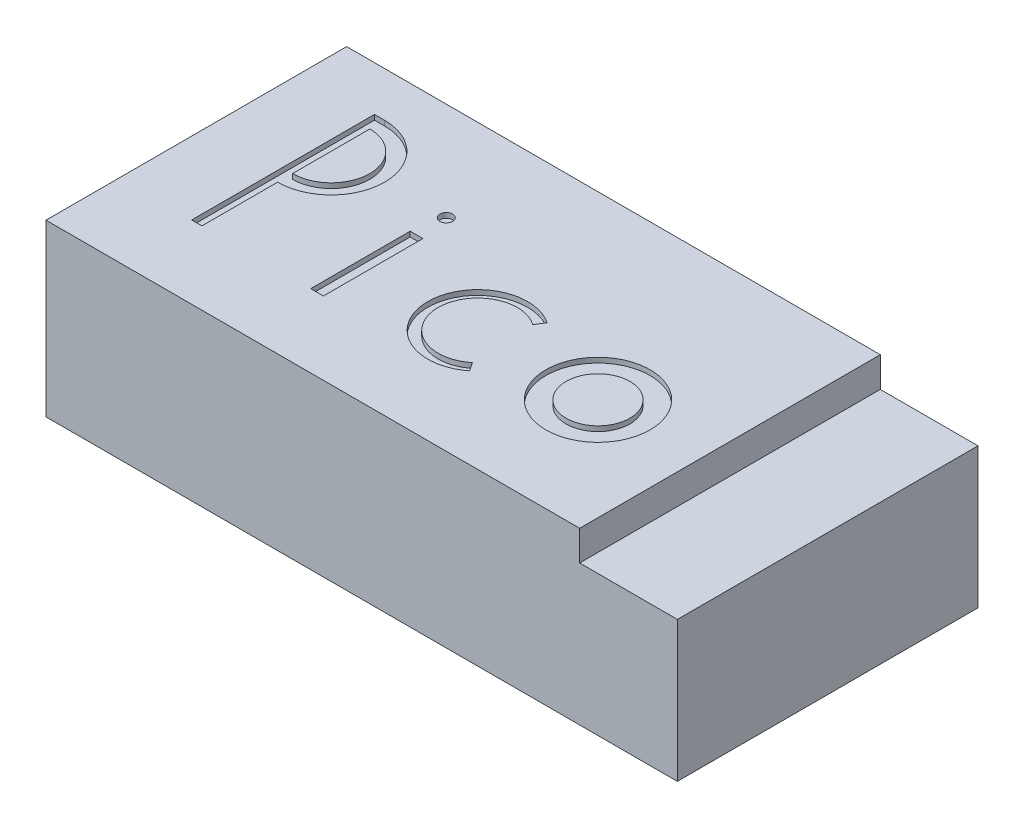
SolidWorks part; units mm, degrees
ref_plane "Front Plane" through (0, 0, 0) normal (0, 0, 1) x (1, 0, 0)
ref_plane "Top Plane" through (0, 0, 0) normal (0, 1, 0) x (1, 0, 0)
ref_plane "Right Plane" through (0, 0, 0) normal (1, 0, 0) x (0, 0, -1)
sketch "Sketch1" plane through (0, 0, 0) normal (0, 1, 0) x (1, 0, 0)
  line L0 (0, 0) -> (126, 0)
  line L1 (126, 0) -> (126, 60)
  line L2 (126, 60) -> (0, 60)
  line L3 (0, 60) -> (0, 0)
  dimension "D1" = 126
  dimension "D2" = 60
extrude "Boss-Extrude1" add sketch "Sketch1" along normal blind 28
sketch "Sketch2" plane through (0, 28, 0) normal (0, 1, 0) x (1, 0, 0)
  line L0 (0, 0) -> (106.5, 0)
  line L1 (0, 0) -> (126, 0) construction
  line L2 (106.5, 0) -> (106.5, 60)
  line L3 (126, 60) -> (0, 60) construction
  line L4 (106.5, 60) -> (0, 60)
  line L5 (0, 60) -> (0, 0)
  dimension "D1" = 106.5
extrude "Boss-Extrude2" add sketch "Sketch2" along normal blind 6
sketch "Sketch3" plane through (0, 34, 0) normal (0, 1, 0) x (1, 0, 0)
  line L0 (14.4991, 40.4296) -> (14.4991, 14.5795)
  line L1 (14.4991, 14.5795) -> (16.5467, 14.5795)
  line L2 (16.5467, 14.5795) -> (16.5467, 29.6801)
  line L3 (14.4991, 40.4296) -> (14.4991, 51.0512)
  line L4 (14.4991, 51.0512) -> (16.5467, 51.0512)
  line L5 (16.5467, 48.0802) -> (16.5467, 32.6511)
  line L6 (38.2463, 34.4352) -> (38.2463, 14.5795)
  line L7 (38.2463, 14.5795) -> (40.7879, 14.5795)
  line L8 (40.7879, 14.5795) -> (40.7879, 34.4352)
  line L9 (40.7879, 34.4352) -> (38.2463, 34.4352)
  line L10 (67.7415, 32.263) -> (66.622, 30.5345)
  line L11 (67.1661, 17.9446) -> (68.3223, 16.2319)
  arc A0 (16.5467, 29.6801) -> (16.5467, 51.0512) centre (16.5467, 40.3656) ccw
  arc A1 (16.5467, 48.0802) -> (16.5467, 32.6511) centre (16.5467, 40.3656) cw
  circle A2 centre (39.5171, 40.3656) radius 1.2708
  arc A3 (68.3223, 16.2319) -> (67.7415, 32.263) centre (62.1212, 24.0333) cw
  arc A4 (66.622, 30.5345) -> (67.1661, 17.9446) centre (62.1212, 24.0333) ccw
  circle A5 centre (86.1255, 24.0333) radius 6.3667
  circle A6 centre (86.1255, 24.0333) radius 10.4019
extrude "Cut-Extrude1" cut sketch "Sketch3" against normal blind 1
